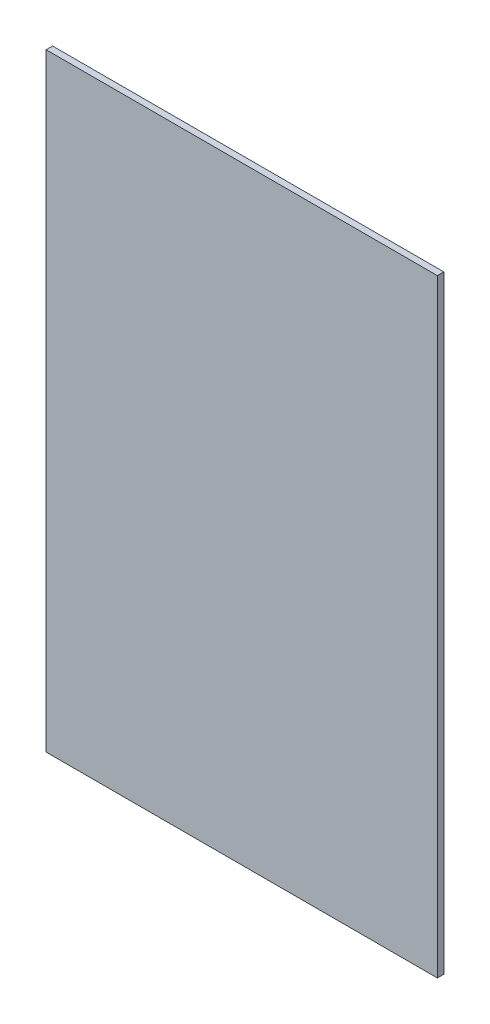
SolidWorks part; units mm, degrees
ref_plane "Alzado" through (0, 0, 0) normal (0, 0, 1) x (1, 0, 0)
ref_plane "Planta" through (0, 0, 0) normal (0, 1, 0) x (1, 0, 0)
ref_plane "Vista lateral" through (0, 0, 0) normal (1, 0, 0) x (0, 0, -1)
sketch "Croquis1" plane through (0, 0, 0) normal (0, 0, 1) x (1, 0, 0)
  line L1 (-302.35, 470) -> (302.35, 470)
  line L2 (-302.35, 470) -> (-302.35, -470)
  line L3 (-302.35, -470) -> (302.35, -470)
  line L4 (302.35, 470) -> (302.35, -470)
  line L5 (-302.35, 470) -> (302.35, -470) construction
  line L6 (-302.35, -470) -> (302.35, 470) construction
  point P0 (0, 0)
  dimension "D1" = 604.7
  dimension "D2" = 940
extrude "Saliente-Extruir1" add sketch "Croquis1" along normal blind 10
